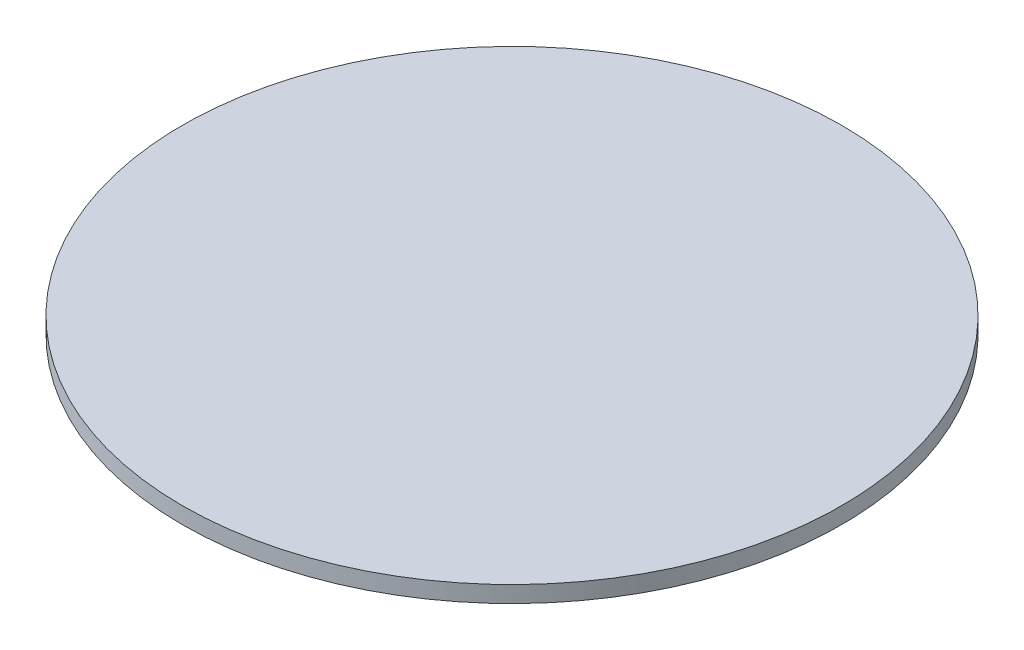
SolidWorks part; units mm, degrees
ref_plane "Front Plane" through (0, 0, 0) normal (0, 0, 1) x (1, 0, 0)
ref_plane "Top Plane" through (0, 0, 0) normal (0, 1, 0) x (1, 0, 0)
ref_plane "Right Plane" through (0, 0, 0) normal (1, 0, 0) x (0, 0, -1)
sketch "Sketch1" plane through (0, 0, 0) normal (0, 1, 0) x (1, 0, 0)
  circle A1 centre (0, 0) radius 127
  dimension "D1" = 254
extrude "Boss-Extrude1" add sketch "Sketch1" along normal blind 6.35
